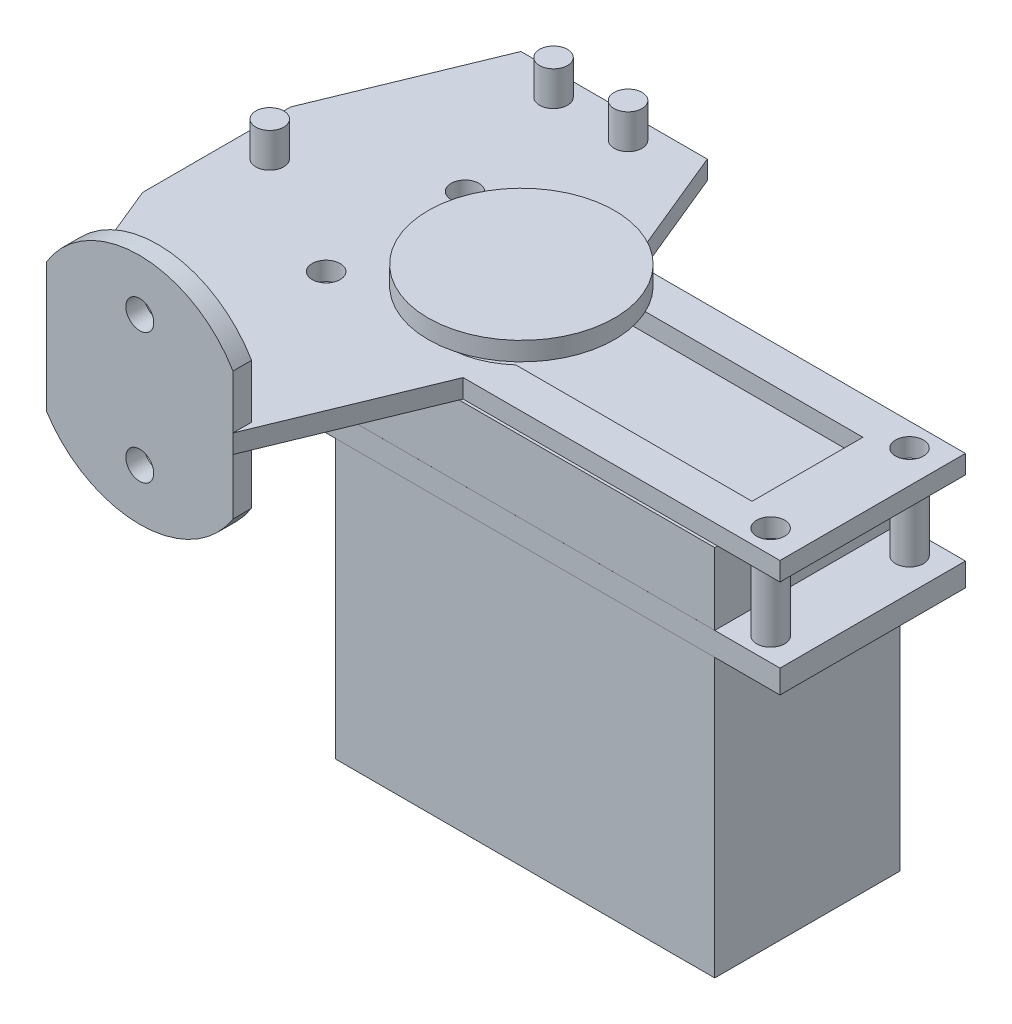
SolidWorks part; units mm, degrees
ref_plane "정면" through (0, 0, 0) normal (0, 0, 1) x (1, 0, 0)
ref_plane "윗면" through (0, 0, 0) normal (0, 1, 0) x (1, 0, 0)
ref_plane "우측면" through (0, 0, 0) normal (1, 0, 0) x (0, 0, -1)
sketch "스케치1" plane through (0, 0, 0) normal (0, 1, 0) x (1, 0, 0)
  line L1 (-20.35, 9.95) -> (20.35, 9.95)
  line L2 (-20.35, 9.95) -> (-20.35, -9.95)
  line L3 (-20.35, -9.95) -> (20.35, -9.95)
  line L4 (20.35, 9.95) -> (20.35, -9.95)
  line L5 (-20.35, 9.95) -> (20.35, -9.95) construction
  line L6 (-20.35, -9.95) -> (20.35, 9.95) construction
  point P0 (0, 0)
  dimension "D1" = 40.7
  dimension "D2" = 19.9
extrude "보스-돌출1" add sketch "스케치1" along normal blind 40
sketch "스케치2" plane through (0, 40, 0) normal (0, 1, 0) x (1, 0, 0)
  line L0 (-20.35, 9.95) -> (-20.35, -9.95) construction
  circle A0 centre (-10.35, 0) radius 3
  dimension "D1" = 6
  dimension "D2" = 10
extrude "보스-돌출2" add sketch "스케치2" along normal blind 6
sketch "스케치3" plane through (0, 40, 0) normal (0, 1, 0) x (1, 0, 0)
  line L0 (-20.35, 9.95) -> (-20.35, -9.95) construction
  line L1 (27.35, -9.9506) -> (-27.35, -9.9506)
  line L2 (27.35, -9.9506) -> (27.35, 9.9506)
  line L3 (27.35, 9.9506) -> (-27.35, 9.9506)
  line L4 (-27.35, -9.9506) -> (-27.35, 9.9506)
  line L5 (27.35, -9.9506) -> (-27.35, 9.9506) construction
  line L6 (27.35, 9.9506) -> (-27.35, -9.9506) construction
  point P0 (0, 0)
  dimension "D1" = 7
  dimension "D2" = 19.9012
extrude "보스-돌출3" add sketch "스케치3" against normal blind 2.5 from offset 7.7 offset against normal yes
sketch "스케치4" plane through (0, 46, 0) normal (0, 1, 0) x (1, 0, 0)
  circle A0 centre (-10.35, 0) radius 10
  dimension "D1" = 20
extrude "보스-돌출4" add sketch "스케치4" against normal blind 2
sketch "스케치5" plane through (0, 32.3, 0) normal (0, 1, 0) x (1, 0, 0)
  line L2 (-27.35, -9.9506) -> (-20.35, -9.95)
  circle A0 centre (23.85, -7.4503) radius 1.5
  circle A1 centre (23.85, 7.4503) radius 1.5
  circle A2 centre (-23.85, -7.4503) radius 1.5
  circle A3 centre (-23.85, 7.4503) radius 1.5
extrude "보스-돌출5" add sketch "스케치5" along normal blind 8 contours A0 | A1 | A2 | A3
ref_plane "평면1" through (0, 40.3, 0) normal (0, 1, 0) x (1, 0, 0)
sketch "스케치7" plane through (0, 40.3, 0) normal (0, 1, 0) x (1, 0, 0)
  line L0 (27.35, -9.9506) -> (27.35, 9.9506) construction
  line L1 (27.35, -9.9506) -> (27.35, 9.9506)
  line L2 (27.35, -9.9506) -> (-6.65, -9.95)
  line L4 (-20.35, -9.95) -> (20.35, -9.95) construction
  line L5 (27.35, 9.9506) -> (-8.2957, 9.95)
  line L9 (20.35, -9.95) -> (20.35, 9.95) construction
  line L10 (20.35, -5.95) -> (-5.0023, -5.95)
  line L11 (-33.85, -27.4503) -> (-13.85, -27.4503)
  line L12 (20.35, -9.95) -> (20.35, 9.95) construction
  line L13 (20.35, 5.95) -> (-5.0023, 5.95)
  line L14 (20.35, 5.95) -> (20.35, -5.95)
  line L15 (-6.65, -9.95) -> (-13.85, -27.4503)
  line L16 (-41.05, -9.95) -> (-33.85, -27.4503)
  line L17 (-41.05, -9.95) -> (-41.05, 5.95)
  line L18 (-8.2957, 9.95) -> (-13.85, 23.4503)
  line L19 (-33.85, 23.4503) -> (-13.85, 23.4503)
  line L20 (-41.05, 5.95) -> (-33.85, 23.4503)
  arc A3 (-5.0023, 5.95) -> (-5.0023, -5.95) centre (-10.35, 0) ccw
  circle A4 centre (-23.85, -7.4503) radius 1.5 construction
  circle A5 centre (-23.85, 7.4503) radius 1.5 construction
  circle A6 centre (23.85, 7.4503) radius 1.5 construction
  circle A7 centre (23.85, -7.4503) radius 1.5 construction
  circle A8 centre (-23.85, -7.4503) radius 1.5
  circle A9 centre (-23.85, 7.4503) radius 1.5
  circle A10 centre (23.85, 7.4503) radius 1.5
  circle A11 centre (23.85, -7.4503) radius 1.5
  point P27 (-23.85, -27.4503)
  dimension "D1" = 16
extrude "보스-돌출6" add sketch "스케치7" along normal blind 2 separate body
sketch "스케치8" plane through (0, 42.3, 0) normal (0, 1, 0) x (1, 0, 0)
  line L5 (-33.85, -27.4503) -> (-13.85, -27.4503)
  line L6 (-13.85, -27.4503) -> (-13.85, -25.4503)
  line L7 (-13.85, -25.4503) -> (-33.85, -25.4503)
  line L8 (-33.85, -25.4503) -> (-33.85, -27.4503)
extrude "보스-돌출7" add sketch "스케치8" along normal blind 11.5
sketch "스케치9" plane through (0, 40.3, 0) normal (0, -1, 0) x (1, 0, 0)
  line L0 (-33.85, 27.4503) -> (-13.85, 27.4503)
  line L1 (-13.85, 27.4503) -> (-13.85, 25.4503)
  line L2 (-13.85, 25.4503) -> (-33.85, 25.4503)
  line L3 (-33.85, 25.4503) -> (-33.85, 27.4503)
extrude "보스-돌출8" add sketch "스케치9" along normal blind 11.5
sketch "스케치10" plane through (0, 0, 27.4503) normal (0, 0, 1) x (1, 0, 0)
  circle A0 centre (-23.85, 41.3) radius 4
  circle A1 centre (-23.85, 34.3) radius 1.5
  circle A2 centre (-30.85, 41.3) radius 1.5
  circle A3 centre (-23.85, 41.3) radius 4
  circle A4 centre (-23.85, 48.3) radius 1.5
  circle A5 centre (-23.85, 41.3) radius 4
  circle A6 centre (-16.85, 41.3) radius 1.5
  circle A7 centre (-23.85, 41.3) radius 4
  point P24 (-23.85, 41.3)
  dimension "D2" = 4
extrude "컷-돌출1" cut sketch "스케치10" against normal blind 6.5 contours A4 | A1
sketch "스케치11" plane through (0, 42.3, 0) normal (0, 1, 0) x (1, 0, 0)
  circle A3 centre (-37.35, 0) radius 1.5
  circle A6 centre (-27.85, 20.9503) radius 1.5
  circle A7 centre (-19.85, 20.9503) radius 1.5
extrude "컷-돌출2" cut sketch "스케치11" against normal blind 6.5
sketch "스케치12" plane through (0, 0, 27.4503) normal (0, 0, 1) x (1, 0, 0)
  line L0 (-33.85, 53.8) -> (-33.85, 42.3) construction
  line L1 (-13.85, 53.8) -> (-13.85, 42.3) construction
  line L2 (-33.85, 34.3) -> (-33.85, 28.8)
  line L3 (-33.85, 28.8) -> (-33.85, 40.3) construction
  line L4 (-13.85, 28.8) -> (-13.85, 40.3) construction
  line L5 (-13.85, 34.3) -> (-13.85, 28.8)
  line L11 (-33.85, 42.3) -> (-33.85, 40.3)
  line L12 (-33.85, 40.3) -> (-33.85, 28.8)
  line L13 (-33.85, 28.8) -> (-13.85, 28.8)
  line L14 (-13.85, 28.8) -> (-13.85, 40.3)
  line L15 (-13.85, 40.3) -> (-13.85, 42.3)
  line L16 (-13.85, 42.3) -> (-13.85, 53.8)
  line L17 (-13.85, 53.8) -> (-33.85, 53.8)
  line L18 (-33.85, 53.8) -> (-33.85, 42.3)
  line L21 (-33.85, 28.8) -> (-13.85, 28.8)
  line L24 (-13.85, 48.05) -> (-13.85, 53.8)
  line L25 (-13.85, 53.8) -> (-33.85, 53.8)
  line L26 (-33.85, 53.8) -> (-33.85, 48.2139)
  arc A0 (-33.85, 48.2139) -> (-13.85, 48.05) centre (-23.8991, 42.1438) cw
  arc A2 (-33.85, 34.3) -> (-13.85, 34.3) centre (-23.85, 40.6409) ccw
  line M13 (-33.85, 40.3) -> (-33.85, 28.8)
  line M14 (-33.85, 28.8) -> (-13.85, 28.8)
  line M15 (-13.85, 28.8) -> (-13.85, 40.3)
  line M17 (-13.85, 42.3) -> (-13.85, 53.8)
  line M18 (-13.85, 53.8) -> (-33.85, 53.8)
  line M19 (-33.85, 53.8) -> (-33.85, 42.3)
  dimension "D1" = 0
extrude "컷-돌출3" cut sketch "스케치12" against normal blind 6.5 contours A2 M13 M14 | A2 L21 M15 | A0 L25 M19 | A0 M18 M17
sketch "스케치15" plane through (0, 42.3, 0) normal (0, 1, 0) x (1, 0, 0)
  circle A0 centre (-27.85, 20.9503) radius 1.5
  circle A1 centre (-19.85, 20.9503) radius 1.5 construction
  circle A2 centre (-19.85, 20.9503) radius 1.5
  circle A3 centre (-37.35, 0) radius 1.5 construction
  circle A4 centre (-37.35, 0) radius 1.5
extrude "보스-돌출9" add sketch "스케치15" along normal blind 3.7 separate body
sketch "스케치16" plane through (0, 46, 0) normal (0, 1, 0) x (1, 0, 0)
  circle A0 centre (-37.35, 0) radius 12.5
  circle A1 centre (-10.35, 0) radius 12.5
  dimension "D1" = 25
  dimension "D2" = 25
